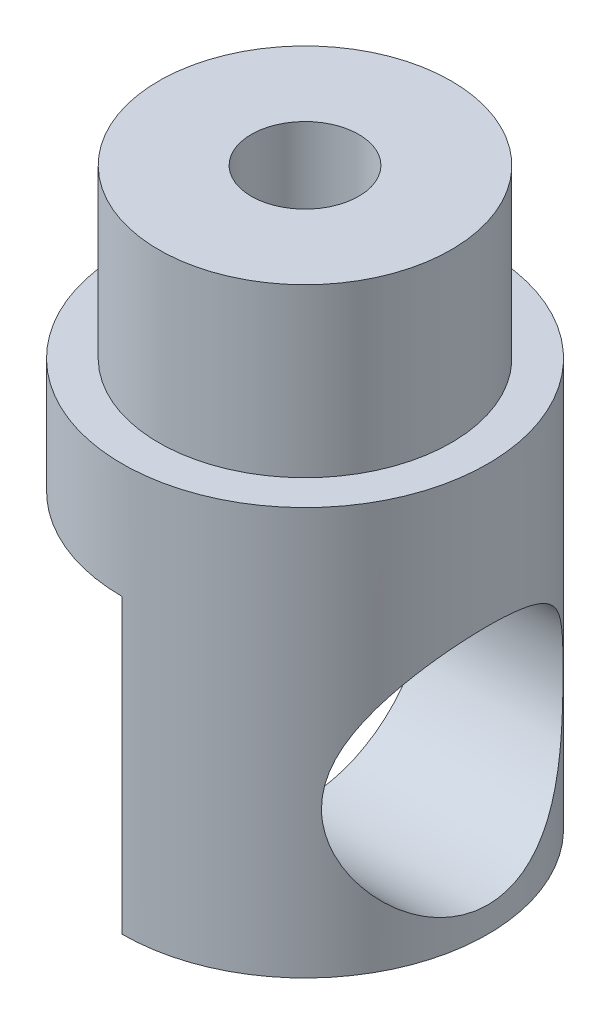
SolidWorks part; units mm, degrees
ref_plane "Front Plane" through (0, 0, 0) normal (0, 0, 1) x (1, 0, 0)
ref_plane "Top Plane" through (0, 0, 0) normal (0, 1, 0) x (1, 0, 0)
ref_plane "Right Plane" through (0, 0, 0) normal (1, 0, 0) x (0, 0, -1)
sketch "Croquis1" plane through (0, 0, 0) normal (0, 1, 0) x (1, 0, 0)
  circle A0 centre (0, 0) radius 11.1125
  dimension "D1" = 22.225
extrude "Saliente-Extruir1" add sketch "Croquis1" along normal blind 34.925
sketch "Croquis12" plane through (0, 34.925, 0) normal (0, -1, 0) x (1, 0, 0)
  circle A0 centre (0, 0) radius 8.89
  circle A1 centre (0, 0) radius 11.1125
  dimension "D1" = 17.78
extrude "Cortar-Extruir2" cut sketch "Croquis12" along normal blind 10.16
hole_wizard "Taladro roscado 5/16-181" positions "Croquis5" profile "Croquis4" tap size "5/16-18" standard "Ansi Inch"
sketch "Croquis5" plane through (0, 34.925, 0) normal (0, 1, 0) x (1, 0, 0)
  point P0 (0, 0)
sketch "Croquis4" plane through (0, 34.925, 0) normal (1, 0, 0) x (0, 0, 1)
  line L0 (0, 0) -> (0, 14.6611)
  line L1 (0, 14.6611) -> (3.2639, 12.7)
  line L2 (3.2639, 12.7) -> (3.2639, 0)
  line L5 (3.2639, 0) -> (0, 0)
  line L10 (0, 14.6611) -> (-3.2639, 12.7) construction
  line L11 (0, -6.35) -> (0, 107.95) construction
  dimension "Diámetro de perforador para roscar" = 6.5278
  dimension "Profundidad de perforador para roscar" = 12.7
  dimension "Ángulo de perforador" = 118
cosmetic thread "Rosca de taladro1" parameters "D1"=12.7, "D2"=7.9375
sketch "Croquis6" plane through (0, 0, 0) normal (1, 0, 0) x (0, 0, -1)
  line L0 (11.1125, 0) -> (11.1125, 24.765) construction
  line L1 (-11.1125, 0) -> (11.1125, 0)
  line L2 (-11.1125, 0) -> (-11.1125, 17.78)
  line L3 (-11.1125, 17.78) -> (11.1125, 17.78)
  line L4 (11.1125, 0) -> (11.1125, 17.78)
  dimension "D1" = 17.78
extrude "Cortar-Extruir1" cut sketch "Croquis6" against normal blind 25.4
hole_wizard "Taladro roscado 5/8-181" positions "Croquis11" profile "Croquis10" tap size "5/8-18" standard "Ansi Inch"
sketch "Croquis11" plane through (0, 0, 0) normal (-1, 0, 0) x (0, 0, 1)
  line L0 (11.1125, 34.925) -> (-11.1125, 34.925) construction
  line L1 (0, 0) -> (0, 15.3596) construction
  point P0 (0, 8.89)
  dimension "D1" = 26.035
sketch "Croquis10" plane through (0, 8.89, 0) normal (0, 1, 0) x (0, 0, 1)
  line L0 (0, 0) -> (0, 43.2099)
  line L1 (0, 43.2099) -> (7.3419, 38.7985)
  line L2 (7.3419, 38.7985) -> (7.3419, 0)
  line L5 (7.3419, 0) -> (0, 0)
  line L10 (0, 43.2099) -> (-7.3419, 38.7985) construction
  line L11 (0, -6.35) -> (0, 107.95) construction
  dimension "Diámetro de perforador para roscar" = 14.6837
  dimension "Profundidad de perforador para roscar" = 38.7985
  dimension "Ángulo de perforador" = 118
cosmetic thread "Rosca de taladro2" parameters "D1"=11.1125, "D2"=15.875
sketch "Croquis13" plane through (0, 0, 0) normal (-1, 0, 0) x (0, 0, 1)
  circle A0 centre (0, 8.89) radius 7.3419
  dimension "D1" = 14.6837
